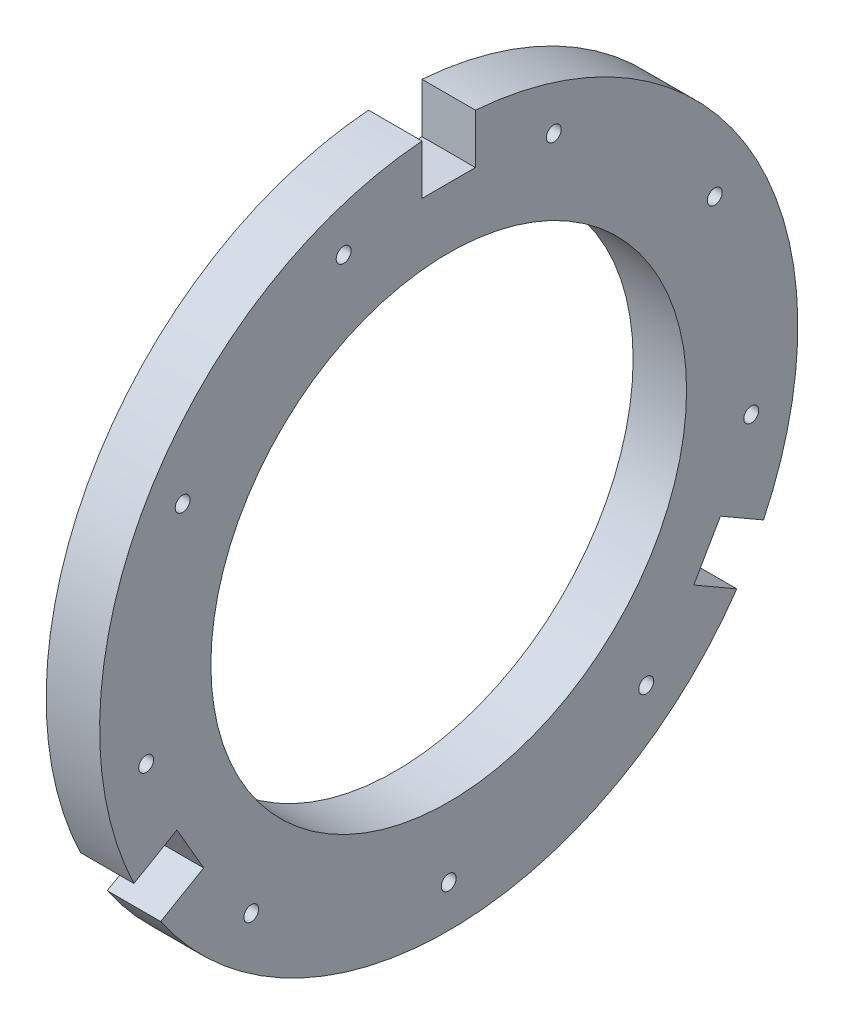
SolidWorks part; units mm, degrees
material "Zoltek Panex 33"
ref_plane "Plan de face" through (0, 0, 0) normal (0, 0, 1) x (1, 0, 0)
ref_plane "Plan de dessus" through (0, 0, 0) normal (0, 1, 0) x (1, 0, 0)
ref_plane "Plan de droite" through (0, 0, 0) normal (1, 0, 0) x (0, 0, -1)
sketch "Esquisse1" plane through (0, 0, 0) normal (1, 0, 0) x (0, 0, -1)
  line L0 (0, 0) -> (0, 51.1) construction
  line L1 (0, 51.1) -> (-5.741, 51.1) construction
  line L2 (-5.741, 51.1) -> (-5.741, 64.1) construction
  line L3 (-5.741, 64.1) -> (-5.741, 74.7799)
  line L4 (-5.741, 64.1) -> (5.741, 64.1)
  line L5 (5.741, 64.1) -> (5.741, 74.7799)
  line L6 (58.3827, -27.0781) -> (67.6318, -32.4181)
  line L7 (58.3827, -27.0781) -> (52.6417, -37.0219)
  line L8 (52.6417, -37.0219) -> (61.8908, -42.3618)
  line L9 (-52.6417, -37.0219) -> (-61.8908, -42.3618)
  line L10 (-52.6417, -37.0219) -> (-58.3827, -27.0781)
  line L11 (-58.3827, -27.0781) -> (-67.6318, -32.4181)
  circle A0 centre (0, 0) radius 51.1
  circle A1 centre (0, 0) radius 75 construction
  arc A2 (-5.741, 74.7799) -> (-67.6318, -32.4181) centre (0, 0) ccw
  arc A3 (-61.8908, -42.3618) -> (61.8908, -42.3618) centre (0, 0) ccw
  arc A4 (67.6318, -32.4181) -> (5.741, 74.7799) centre (0, 0) ccw
  point P20 (0, 0)
  dimension "D1" = 102.2
  dimension "D2" = 150
  dimension "D3" = 5.741
  dimension "D4" = 13
  dimension "D5" = 11.482
  dimension "D6" = 3
extrude "Boss.-Extru.1" add sketch "Esquisse1" along normal blind 11.482
sketch "Sketch1" plane through (0, 0, 0) normal (1, 0, 0) x (0, 0, -1)
  line L0 (0, 0) -> (0, 40) construction
  line L1 (0, 0) -> (22.5733, 62.0197) construction
  circle A0 centre (22.5733, 62.0197) radius 1.6
  circle A1 centre (57.1577, 33) radius 1.6
  circle A2 centre (64.9973, -11.4608) radius 1.6
  circle A3 centre (42.424, -50.5589) radius 1.6
  circle A4 centre (0, -66) radius 1.6
  circle A5 centre (-42.424, -50.5589) radius 1.6
  circle A6 centre (-64.9973, -11.4608) radius 1.6
  circle A7 centre (-57.1577, 33) radius 1.6
  circle A8 centre (-22.5733, 62.0197) radius 1.6
  point P23 (0, 0)
  dimension "D4" = 3.2
  dimension "D1" = 40
  dimension "D2" = 66
  dimension "D3" = 20
  dimension "D5" = 9
extrude "Cut-Extrude1" cut sketch "Sketch1" against normal through all and the other way through all
sketch "Esquisse4" plane through (0, 0, 0) normal (1, 0, 0) x (0, 0, -1)
  line L0 (0, 0) -> (-57.1577, 33) construction
  line L1 (0, 0) -> (0, 41.2211) construction
  line L2 (-57.1577, 33) -> (-54.6577, 37.3301) construction
  line L3 (-57.1577, 33) -> (-59.6577, 28.6699) construction
  circle A0 centre (-57.1577, 33) radius 5
  dimension "D1" = 10
  dimension "D2" = 66
  dimension "D3" = 60
extrude "Enlèv. mat.-Extru.3" [suppressed] cut sketch "Esquisse4" against normal through all and the other way through all
equation "\"d_i_tube\"= 150mm'Inner Rocket Body Composite Tube Diameter"
equation "\"t_tube\"= 1.182mm'Thickness of Rocket Body Composite Tube"
equation "\"l_upper_body_tube\"= 949.3mm'Upper Rocket Body Composite Tube length"
equation "\"l_lower_body_tube\"= 816mm'Lower Rocket Body Composite Tube Length"
equation "\"d_a_NC\"= 154mm'Outer Diameter of Nosecone base"
equation "\"d_i_phenolic_tube\"= 152.3mm'Inner Phenolic Tube Diameter"
equation "\"t_phenolic_tube\"= 2mm'Thickness of Phenolic Body Tube"
equation "\"l_fin_cut\"= 220mm'Length of fin on Motor Retainer"
equation "\"t_SW-Panel\"= 11.482mm'Thickness of Sandwich-Panel"
equation "\"l_motor_tube\"=610mm'Length of phenolic motor tube"
equation "\"d_i_motor_tube\"=99.06mm'Inner diameter of phenolic motor tube"
equation "\"t_motor_tube\"=1.58mm'Thicknes of phenolic motor tube"
equation "\"D2@Esquisse1\"=\"d_i_tube\""
equation "\"l_cut_fin_centering\"=13mm'Length of cut for fin alignement on fin centering rings"
equation "\"D3@Esquisse1\"= \"t_SW-Panel\" / 2"
equation "\"D4@Esquisse1\"=\"l_cut_fin_centering\""
equation "\"D5@Esquisse1\"=\"t_SW-Panel\""
equation "\"D1@Boss.-Extru.1\"=\"t_SW-Panel\""
